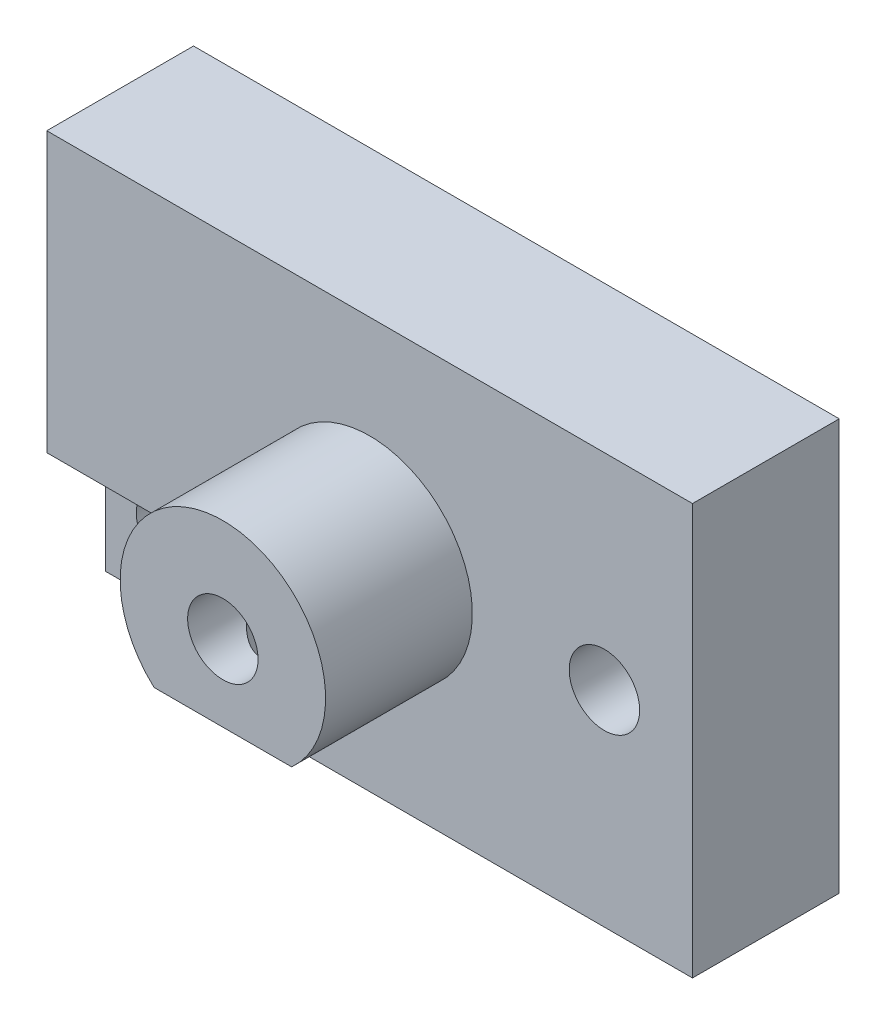
SolidWorks part; units mm, degrees
ref_plane "Спереди" through (0, 0, 0) normal (0, 0, 1) x (1, 0, 0)
ref_plane "Сверху" through (0, 0, 0) normal (0, 1, 0) x (1, 0, 0)
ref_plane "Справа" through (0, 0, 0) normal (1, 0, 0) x (0, 0, -1)
sketch "Эскиз1" plane through (0, 0, 0) normal (0, 0, 1) x (1, 0, 0)
  line L1 (-55, -35) -> (55, -35)
  line L2 (-55, -35) -> (-55, 35)
  line L3 (-55, 35) -> (55, 35)
  line L4 (55, -35) -> (55, 35)
  line L5 (-55, -35) -> (55, 35) construction
  line L6 (-55, 35) -> (55, -35) construction
  point P0 (0, 0)
  dimension "D1" = 110
  dimension "D2" = 70
extrude "Бобышка-Вытянуть1" add sketch "Эскиз1" along normal blind 25
sketch "Эскиз2" plane through (0, 0, 25) normal (0, 0, 1) x (1, 0, 0)
  circle A0 centre (0, 0) radius 17.5
  dimension "D1" = 35
extrude "Бобышка-Вытянуть2" add sketch "Эскиз2" along normal blind 25
sketch "Эскиз3" plane through (0, 0, 50) normal (0, 0, 1) x (1, 0, 0)
  circle A0 centre (0, 0) radius 6
  dimension "D1" = 12
extrude "Вырез-Вытянуть1" cut sketch "Эскиз3" against normal through all
sketch "Эскиз5" plane through (0, 0, 25) normal (0, 0, 1) x (1, 0, 0)
  line L1 (-77.5, -57.5) -> (-32.5, -57.5)
  line L2 (-77.5, -57.5) -> (-77.5, -12.5)
  line L3 (-77.5, -12.5) -> (-32.5, -12.5)
  line L4 (-32.5, -57.5) -> (-32.5, -12.5)
  line L5 (-77.5, -57.5) -> (-32.5, -12.5) construction
  line L6 (-77.5, -12.5) -> (-32.5, -57.5) construction
  point P0 (-55, -35)
  dimension "D1" = 45
extrude "Вырез-Вытянуть3" cut sketch "Эскиз5" against normal blind 10
sketch "Эскиз6" plane through (0, 0, 15) normal (0, 0, 1) x (1, 0, 0)
  line L2 (-43.75, -12.5) -> (-43.75, -35) construction
  line L3 (-32.5, -12.5) -> (-55, -12.5) construction
  line L4 (-32.5, -35) -> (-55, -35) construction
  circle A0 centre (-43.75, -23.75) radius 6
  dimension "D3" = 12
extrude "Вырез-Вытянуть4" cut sketch "Эскиз6" against normal through all
sketch "Эскиз7" plane through (0, 0, 25) normal (0, 0, 1) x (1, 0, 0)
  line L0 (0, 0) -> (40, 0) construction
  circle A0 centre (40, 0) radius 6
  dimension "D1" = 12
  dimension "D2" = 40
extrude "Вырез-Вытянуть5" cut sketch "Эскиз7" against normal through all
sketch "Эскиз8" plane through (0, 0, 50) normal (0, 0, 1) x (1, 0, 0)
  line L0 (-11.7154, -13) -> (11.7154, -13)
  circle A0 centre (0, 0) radius 17.5 construction
  arc A1 (-11.7154, -13) -> (11.7154, -13) centre (0, 0) ccw
  dimension "D1" = 13
extrude "Вырез-Вытянуть6" cut sketch "Эскиз8" against normal up to surface (25 mm away) up to face at (46, 0, 25)
sketch "Эскиз9" plane through (0, -13, 0) normal (0, -1, 0) x (1, 0, 0)
  line L0 (0, 50) -> (0, 25) construction
  line L1 (11.7154, 50) -> (-11.7154, 50) construction
  line L2 (11.7154, 25) -> (-11.7154, 25) construction
  circle A0 centre (0, 37.5) radius 6
  dimension "D1" = 12
extrude "Вырез-Вытянуть7" cut sketch "Эскиз9" against normal up to next
